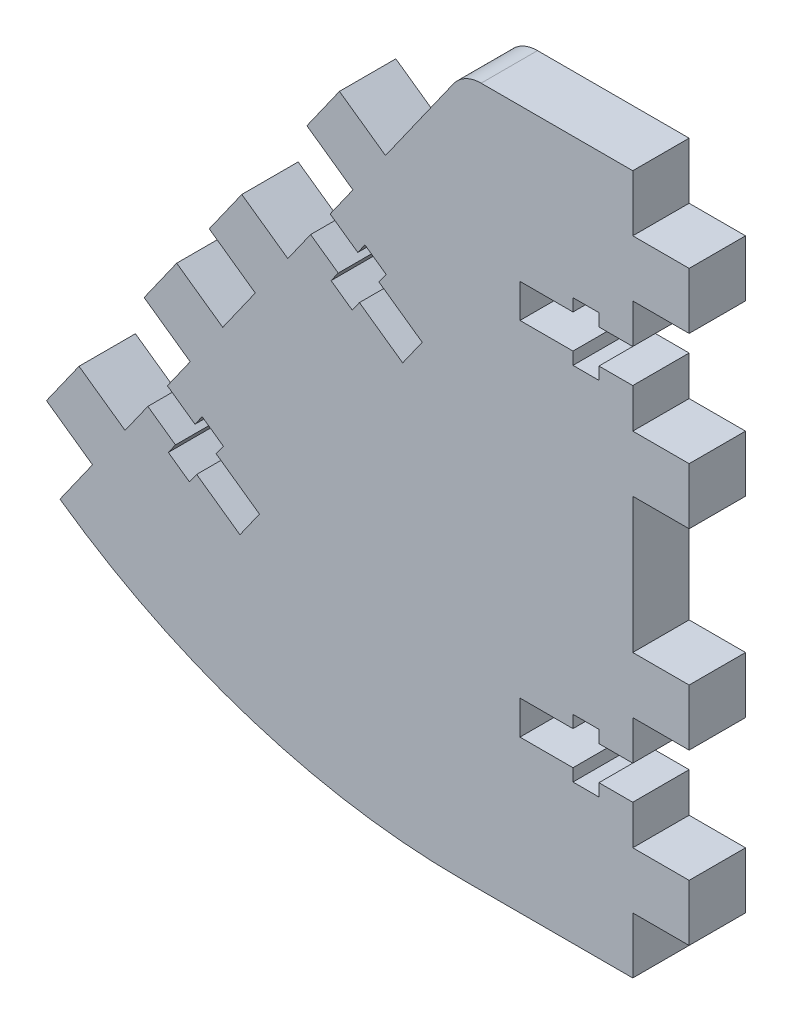
SolidWorks part; units mm, degrees
ref_plane "Front" through (0, 0, 0) normal (0, 0, 1) x (1, 0, 0)
ref_plane "Top" through (0, 0, 0) normal (0, 1, 0) x (1, 0, 0)
ref_plane "Right" through (0, 0, 0) normal (1, 0, 0) x (0, 0, -1)
sketch "Esquisse1" plane through (0, 0, 0) normal (0, 0, 1) x (1, 0, 0)
  line L0 (-33.4752, -26.1279) -> (-15, 0) construction
  line L1 (0, 0) -> (0, -57) construction
  line L2 (0, -5) -> (0, 0)
  line L3 (-15, 0) -> (0, 0) construction
  line L4 (-33.4752, -26.1279) -> (-36.362, -30.2104)
  line L5 (0, -25) -> (0, -37)
  line L6 (-21.9282, -9.798) -> (-15, 0)
  line L7 (-15, 0) -> (0, 0)
  line L8 (0, -57) -> (0, -62)
  line L9 (0, -62) -> (-15, -62) construction
  line L10 (-50.7957, -50.6228) -> (-53.7002, -48.569) construction
  line L11 (-50.7957, -50.6228) -> (-47.909, -46.5403)
  line L12 (-15, -62) -> (0, -62)
  arc A0 (-50.7957, -50.6228) -> (-15, -62) centre (-15, 0) ccw
  point P2 (-12.6826, -62)
  line B0 (-3, -17.6) -> (-5.3, -17.6)
  line B1 (-5.3, -13.5) -> (-10, -13.5)
  line B2 (-10, -16.5) -> (-5.3, -16.5)
  line B3 (-5.3, -17.6) -> (-5.3, -16.5)
  line B4 (0, -15) -> (-11.2208, -15) construction
  line B5 (0, -16.5) -> (0, -20)
  line B6 (5, -20) -> (5, -25)
  line B7 (5, -25) -> (0, -25)
  line B8 (5, -20) -> (0, -20)
  line B9 (0, -13.5) -> (0, -10)
  line B10 (0, -10) -> (5, -10)
  line B11 (5, -10) -> (5, -5)
  line B12 (5, -5) -> (0, -5)
  line B13 (0, -16.5) -> (0, -13.5) construction
  line B14 (0, -13.5) -> (-3, -13.5)
  line B15 (-5.3, -13.5) -> (-5.3, -12.4)
  line B16 (-3, -12.4) -> (-3, -13.5)
  line B17 (-10, -13.5) -> (-10, -16.5)
  line B18 (-3, -16.5) -> (-3, -17.6)
  line B19 (-5.3, -12.4) -> (-3, -12.4)
  line B20 (-3, -16.5) -> (0, -16.5)
  line B21 (-10, -15) -> (0, -15) construction
  line B22 (-3, -49.6) -> (-5.3, -49.6)
  line B23 (-5.3, -45.5) -> (-10, -45.5)
  line B24 (-10, -48.5) -> (-5.3, -48.5)
  line B25 (-5.3, -49.6) -> (-5.3, -48.5)
  line B26 (0, -47) -> (-11.2208, -47) construction
  line B27 (0, -48.5) -> (0, -52)
  line B28 (5, -52) -> (5, -57)
  line B29 (5, -57) -> (0, -57)
  line B30 (5, -52) -> (0, -52)
  line B31 (0, -45.5) -> (0, -42)
  line B32 (0, -42) -> (5, -42)
  line B33 (5, -42) -> (5, -37)
  line B34 (5, -37) -> (0, -37)
  line B35 (0, -48.5) -> (0, -45.5) construction
  line B36 (0, -45.5) -> (-3, -45.5)
  line B37 (-5.3, -45.5) -> (-5.3, -44.4)
  line B38 (-3, -44.4) -> (-3, -45.5)
  line B39 (-10, -45.5) -> (-10, -48.5)
  line B40 (-3, -48.5) -> (-3, -49.6)
  line B41 (-5.3, -44.4) -> (-3, -44.4)
  line B42 (-3, -48.5) -> (0, -48.5)
  line B43 (-10, -47) -> (0, -47) construction
  line B44 (-23.7511, -17.5721) -> (-21.8732, -18.9)
  line B45 (-24.2403, -22.2476) -> (-20.4028, -24.9612)
  line B46 (-18.6707, -22.5117) -> (-22.5082, -19.7981)
  line B47 (-21.8732, -18.9) -> (-22.5082, -19.7981)
  line B48 (-27.7017, -17.9629) -> (-18.54, -24.4412) construction
  line B49 (-26.8357, -16.7382) -> (-24.815, -13.8804)
  line B50 (-28.8974, -10.9937) -> (-26.0107, -6.9112)
  line B51 (-26.0107, -6.9112) -> (-21.9282, -9.798)
  line B52 (-28.8974, -10.9937) -> (-24.815, -13.8804)
  line B53 (-28.5677, -19.1877) -> (-30.5885, -22.0454)
  line B54 (-30.5885, -22.0454) -> (-34.6709, -19.1587)
  line B55 (-34.6709, -19.1587) -> (-37.5577, -23.2411)
  line B56 (-37.5577, -23.2411) -> (-33.4752, -26.1279)
  line B57 (-26.8357, -16.7382) -> (-28.5677, -19.1877) construction
  line B58 (-28.5677, -19.1877) -> (-26.1182, -20.9197)
  line B59 (-24.2403, -22.2476) -> (-24.8754, -23.1458)
  line B60 (-26.7533, -21.8179) -> (-26.1182, -20.9197)
  line B61 (-20.4028, -24.9612) -> (-18.6707, -22.5117)
  line B62 (-24.3862, -18.4702) -> (-23.7511, -17.5721)
  line B63 (-24.8754, -23.1458) -> (-26.7533, -21.8179)
  line B64 (-24.3862, -18.4702) -> (-26.8357, -16.7382)
  line B65 (-19.5367, -23.7364) -> (-27.7017, -17.9629) construction
  line B66 (-38.1849, -37.9845) -> (-36.3069, -39.3124)
  line B67 (-38.6741, -42.66) -> (-34.8365, -45.3736)
  line B68 (-33.1045, -42.9241) -> (-36.942, -40.2106)
  line B69 (-36.3069, -39.3124) -> (-36.942, -40.2106)
  line B70 (-42.1355, -38.3753) -> (-32.9737, -44.8537) construction
  line B71 (-41.2694, -37.1506) -> (-39.2487, -34.2929)
  line B72 (-43.3312, -31.4061) -> (-40.4444, -27.3236)
  line B73 (-40.4444, -27.3236) -> (-36.362, -30.2104)
  line B74 (-43.3312, -31.4061) -> (-39.2487, -34.2929)
  line B75 (-43.0015, -39.6001) -> (-45.0222, -42.4578)
  line B76 (-45.0222, -42.4578) -> (-49.1047, -39.5711)
  line B77 (-49.1047, -39.5711) -> (-51.9914, -43.6536)
  line B78 (-51.9914, -43.6536) -> (-47.909, -46.5403)
  line B79 (-41.2694, -37.1506) -> (-43.0015, -39.6001) construction
  line B80 (-43.0015, -39.6001) -> (-40.552, -41.3321)
  line B81 (-38.6741, -42.66) -> (-39.3091, -43.5582)
  line B82 (-41.1871, -42.2303) -> (-40.552, -41.3321)
  line B83 (-34.8365, -45.3736) -> (-33.1045, -42.9241)
  line B84 (-38.8199, -38.8826) -> (-38.1849, -37.9845)
  line B85 (-39.3091, -43.5582) -> (-41.1871, -42.2303)
  line B86 (-38.8199, -38.8826) -> (-41.2694, -37.1506)
  line B87 (-33.9705, -44.1488) -> (-42.1355, -38.3753) construction
  dimension "D3" = 5
  dimension "D7" = 32
  dimension "D1" = 15
  dimension "D2" = 35.264
  dimension "D4" = 5
  dimension "D5" = 5
  dimension "D6" = 5
sketch_block_instance "Insert M3 plots ep 5mm-1"
sketch_block "Insert M3 plots ep 5mm" parameters "D1"=10, "D2"=5, "D3"=5
sketch_block_instance "Decoupe Insert M3-4"
sketch_block "Decoupe Insert M3" parameters "D1"=5.2, "D2"=3, "D3"=2.3, "D4"=3, "D5"=10
sketch_block_instance "Insert M3 plots ep 5mm-3"
sketch_block_instance "Insert M3 plots ep 5mm-4"
sketch_block_instance "Insert M3 plots ep 5mm-5"
extrude "Boss.-Extru.1" add sketch "Esquisse1" along normal blind 5
fillet "Congé1" radius 3 1 edges at (-15, 0, 2.5)
